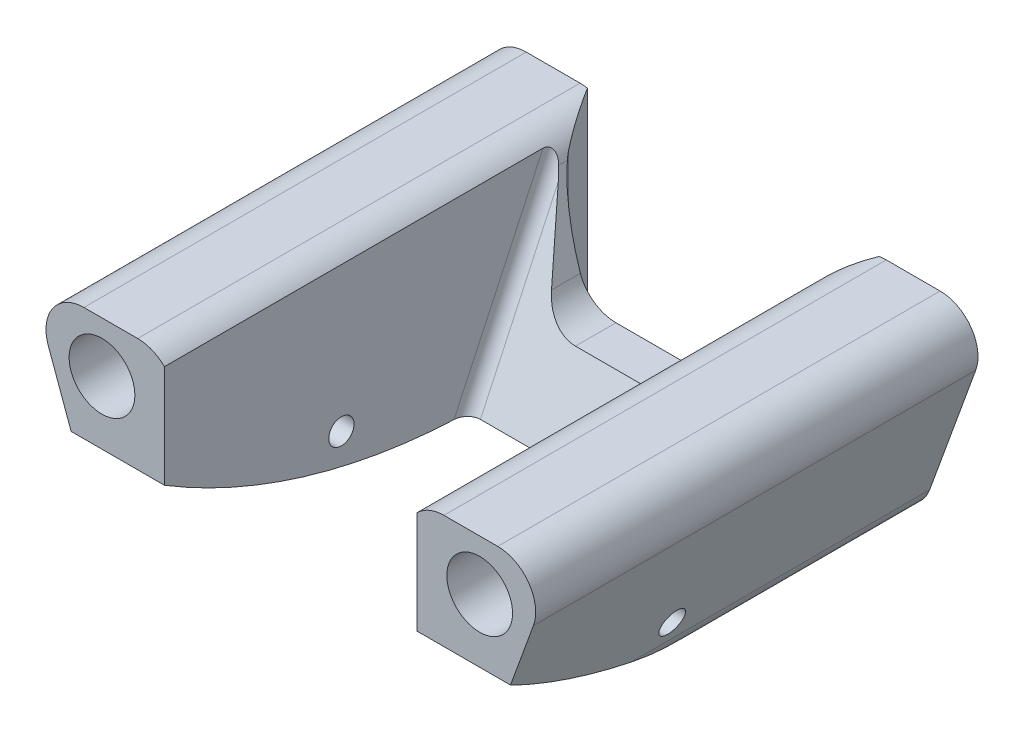
SolidWorks part; units mm, degrees
ref_plane "Front Plane" through (0, 0, 0) normal (0, 0, 1) x (1, 0, 0)
ref_plane "Top Plane" through (0, 0, 0) normal (0, 1, 0) x (1, 0, 0)
ref_plane "Right Plane" through (0, 0, 0) normal (1, 0, 0) x (0, 0, -1)
sketch "Sketch1" plane through (0, 0, 0) normal (0, 0, 1) x (1, 0, 0)
  line L0 (-19.1913, -37.0261) -> (-15.5516, -47.0261)
  line L1 (-12.7325, -49) -> (12.7325, -49)
  line L2 (15.5516, -47.0261) -> (19.1913, -37.0261)
  line L3 (-16.3722, -33) -> (-12.1155, -33)
  line L4 (-9.2964, -34.9739) -> (-7.0937, -41.0261)
  line L5 (-4.2746, -43) -> (4.2746, -43)
  line L6 (7.0937, -41.0261) -> (9.2964, -34.9739)
  line L7 (12.1155, -33) -> (16.3722, -33)
  circle A0 centre (-14.9441, -37) radius 2.6 construction
  circle A1 centre (-14.9441, -37) radius 2.6
  circle A2 centre (14.9441, -37) radius 2.6 construction
  circle A3 centre (14.9441, -37) radius 2.6
  arc A4 (12.7325, -49) -> (15.5516, -47.0261) centre (12.7325, -46) ccw
  arc A5 (-15.5516, -47.0261) -> (-12.7325, -49) centre (-12.7325, -46) ccw
  arc A6 (19.1913, -37.0261) -> (16.3722, -33) centre (16.3722, -36) ccw
  arc A7 (-19.1913, -37.0261) -> (-16.3722, -33) centre (-16.3722, -36) cw
  arc A8 (-9.2964, -34.9739) -> (-12.1155, -33) centre (-12.1155, -36) ccw
  arc A9 (12.1155, -33) -> (9.2964, -34.9739) centre (12.1155, -36) ccw
  arc A10 (4.2746, -43) -> (7.0937, -41.0261) centre (4.2746, -40) ccw
  arc A11 (-7.0937, -41.0261) -> (-4.2746, -43) centre (-4.2746, -40) ccw
  dimension "D1" = 4
  dimension "D2" = 4
  dimension "D3" = 12
  dimension "D10" = 3
  dimension "D4" = 110
  dimension "D5" = 110
  dimension "D6" = 4
  dimension "D7" = 10
  dimension "D8" = 10
  dimension "D9" = 6
extrude "Boss-Extrude1" add sketch "Sketch1" along normal up to surface (35 mm away)
sketch "Sketch4" plane through (0, 0, 0) normal (1, 0, 0) x (0, 0, -1)
  line L0 (-35, -33) -> (0, -33) construction
  line L1 (-35, -49) -> (-11, -49)
  line L2 (-35, -49) -> (-35, -33)
  line L3 (-35, -33) -> (-3.5391, -33)
  line L5 (-11, -49) -> (-3.5391, -33)
  point P7 (-3.829, -33)
extrude "Cut-Extrude3" cut sketch "Sketch4" against normal mid plane 20
sketch "Sketch5" plane through (10, 0, 0) normal (-1, 0, 0) x (0, 0, 1)
  circle A0 centre (21, -45.3) radius 1 construction
  circle A1 centre (21, -45.3) radius 1
extrude "Cut-Extrude4" cut sketch "Sketch5" against normal through all both and the other way through all
sketch "Sketch6" plane through (0, -49, 0) normal (0, -1, 0) x (1, 0, 0)
  line L0 (-12.7325, 0) -> (12.7325, 0) construction
  line L1 (-11.5325, 0) -> (11.5325, 0)
  line L3 (-8.6458, 5) -> (8.6458, 5)
  line L7 (-11.5325, 0) -> (-8.6458, 5)
  line L8 (11.5325, 0) -> (8.6458, 5)
  dimension "D4" = 60
  dimension "D5" = 60
extrude "Cut-Extrude5" cut sketch "Sketch6" against normal through all
fillet "Fillet1" radius 3 2 edges at (-8.6458, -42.8808, 5) (8.6458, -42.8808, 5)
sketch "Sketch7" plane through (10, 0, 0) normal (-1, 0, 0) x (0, 0, 1)
  line L0 (38, -42) -> (35, -42) construction
  line L1 (38, -42) -> (35, -42) construction
  line L3 (35, -49) -> (0, -49) construction
  line L4 (10, -49) -> (0, -49) construction
  line L5 (35, -47.0261) -> (35, -37.0261) construction
  line L6 (35, -42) -> (35, -49)
  line L7 (35, -49) -> (10, -49)
  arc A0 (35, -42) -> (10, -49) centre (10, -0.8571) cw
  dimension "D1" = 25
extrude "Cut-Extrude6" cut sketch "Sketch7" against normal through all both and the other way through all
fillet "Fillet2" radius 1 2 edges at (-10, -41.4313, 7.4707) (10, -41.4313, 7.4707)
